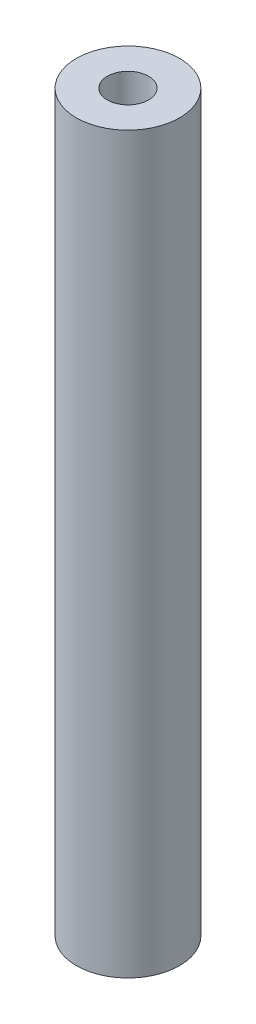
SolidWorks part; units mm, degrees
ref_plane "前视基准面" through (0, 0, 0) normal (0, 0, 1) x (1, 0, 0)
ref_plane "上视基准面" through (0, 0, 0) normal (0, 1, 0) x (1, 0, 0)
ref_plane "右视基准面" through (0, 0, 0) normal (1, 0, 0) x (0, 0, -1)
sketch "草图1" plane through (0, 0, 0) normal (0, 1, 0) x (1, 0, 0)
  circle A0 centre (0, 0) radius 6.25
  dimension "D1" = 12.5
extrude "凸台-拉伸1" add sketch "草图1" along normal blind 89
sketch "草图2" plane through (0, 89, 0) normal (0, 1, 0) x (1, 0, 0)
  circle A0 centre (0, 0) radius 2.5
  circle A1 centre (0, 0) radius 6.25 construction
  dimension "D1" = 5
extrude "切除-拉伸1" cut sketch "草图2" against normal blind 10
cosmetic thread "装饰螺纹线1" parameters "D1"=10, "D2"=6
sketch "草图17" plane through (0, 0, 0) normal (0, -1, 0) x (1, 0, 0)
  circle A0 centre (0, 0) radius 2.5
  dimension "D1" = 5
extrude "切除-拉伸2" cut sketch "草图17" against normal blind 10
cosmetic thread "装饰螺纹线2" parameters "D1"=10, "D2"=6
